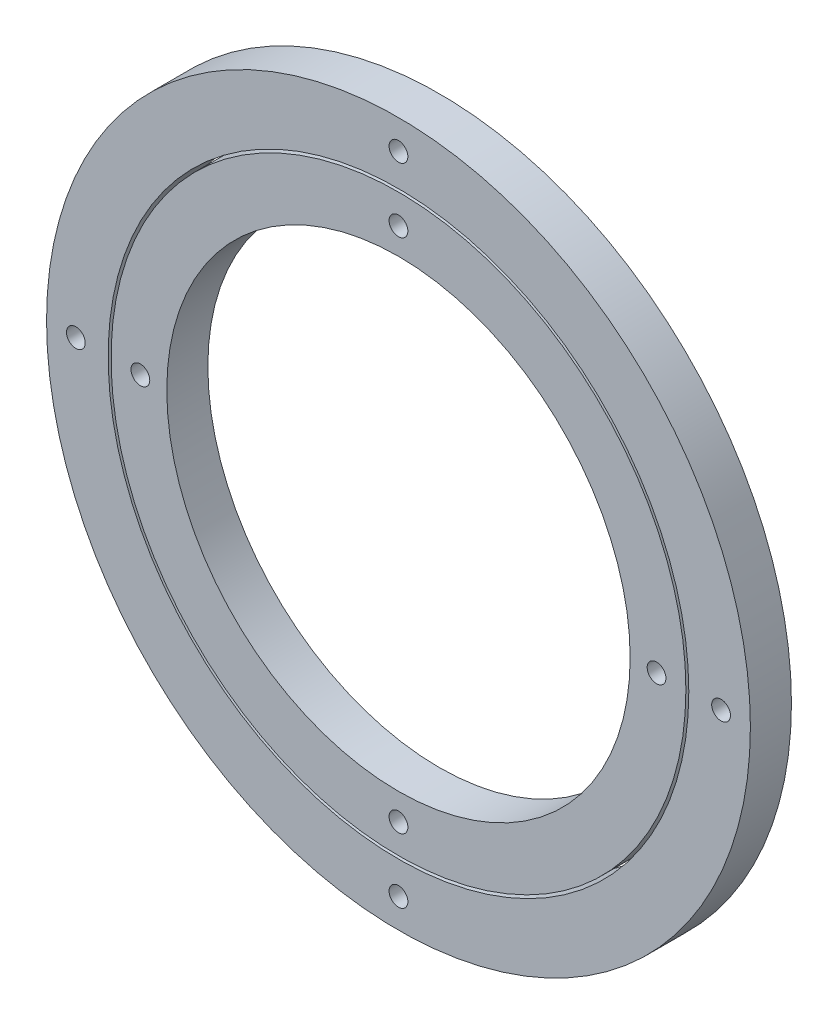
SolidWorks part; units mm, degrees
ref_plane "前视基准面" through (0, 0, 0) normal (0, 0, 1) x (1, 0, 0)
ref_plane "上视基准面" through (0, 0, 0) normal (0, 1, 0) x (1, 0, 0)
ref_plane "右视基准面" through (0, 0, 0) normal (1, 0, 0) x (0, 0, -1)
sketch "草图1" plane through (0, 0, 0) normal (0, 0, 1) x (1, 0, 0)
  circle A0 centre (0, 0) radius 39.5
  circle A3 centre (0, 0) radius 60
  circle A4 centre (0, 55) radius 1.6
  circle A5 centre (55, 0) radius 1.6
  circle A6 centre (0, -55) radius 1.6
  circle A7 centre (-55, 0) radius 1.6
  circle A8 centre (0, 44) radius 1.6
  circle A9 centre (44, 0) radius 1.6
  circle A10 centre (0, -44) radius 1.6
  circle A11 centre (-44, 0) radius 1.6
  point P16 (0, 0)
  point P26 (0, 0)
  dimension "D1" = 4
  dimension "D2" = 4
extrude "凸台-拉伸4" add sketch "草图1" along normal blind 7
sketch "草图2" plane through (0, 0, 0) normal (0, 0, 1) x (1, 0, 0)
  circle A0 centre (0, 0) radius 49
  circle A1 centre (0, 0) radius 49.5
extrude "切除-拉伸1" cut sketch "草图2" along normal blind 15
